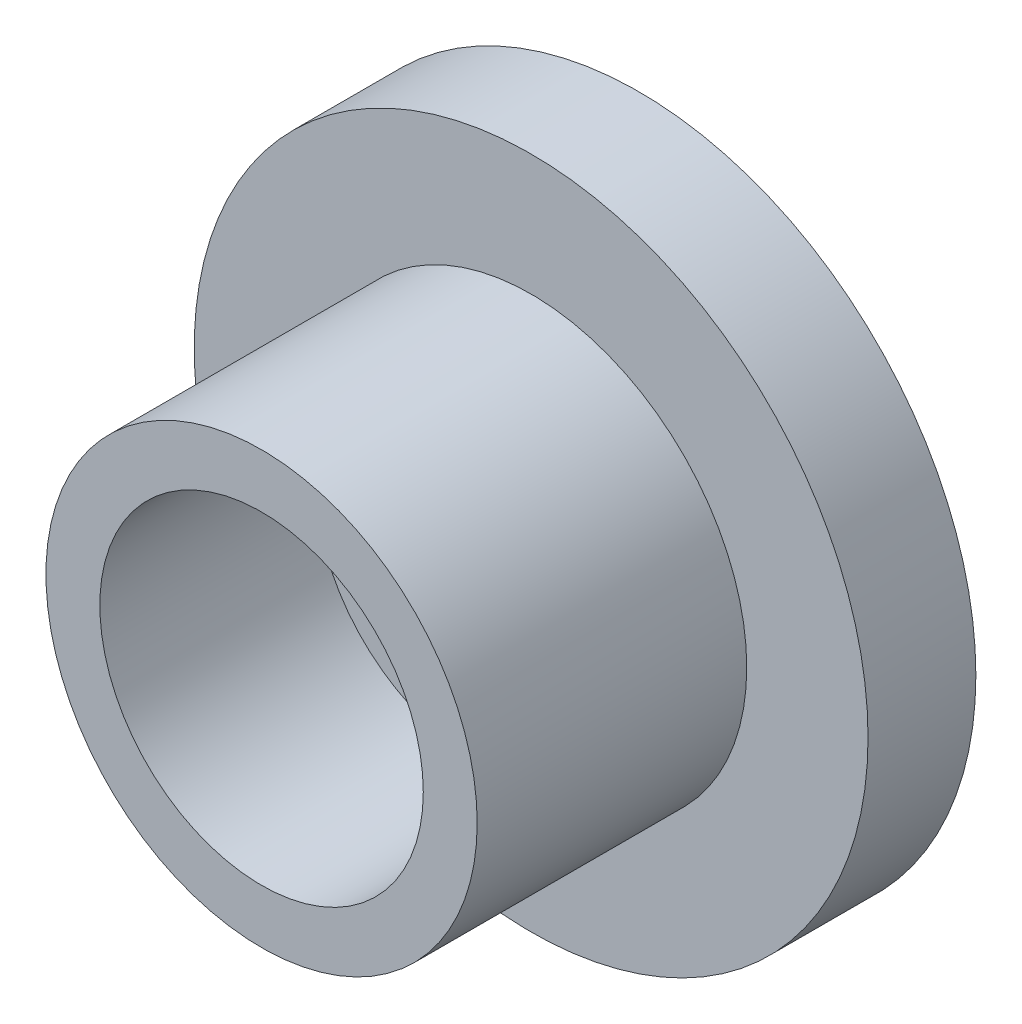
SolidWorks part; units mm, degrees
ref_plane "前视" through (0, 0, 0) normal (0, 0, 1) x (1, 0, 0)
ref_plane "上视" through (0, 0, 0) normal (0, 1, 0) x (1, 0, 0)
ref_plane "右视" through (0, 0, 0) normal (1, 0, 0) x (0, 0, -1)
sketch "草图1" plane through (0, 0, 0) normal (0, 0, 1) x (1, 0, 0)
  circle A0 centre (0, 0) radius 12.5
  dimension "D1" = 25
extrude "凸台-拉伸1" add sketch "草图1" along normal blind 4
sketch "草图2" plane through (0, 0, 4) normal (0, 0, 1) x (1, 0, 0)
  circle A0 centre (0, 0) radius 8
  dimension "D1" = 16
extrude "凸台-拉伸2" add sketch "草图2" along normal blind 10
sketch "草图3" plane through (0, 0, 14) normal (0, 0, 1) x (1, 0, 0)
  circle A0 centre (0, 0) radius 2.5
  dimension "D1" = 5
extrude "切除-拉伸1" cut sketch "草图3" against normal through all
sketch "草图4" plane through (0, 0, 14) normal (0, 0, 1) x (1, 0, 0)
  circle A0 centre (0, 0) radius 6
  dimension "D1" = 12
extrude "切除-拉伸2" cut sketch "草图4" against normal blind 8
sketch "草图5" plane through (0, 0, 0) normal (0, 0, -1) x (-1, 0, 0)
  circle A0 centre (0, 0) radius 6
  dimension "D1" = 12
extrude "切除-拉伸3" cut sketch "草图5" against normal blind 5
